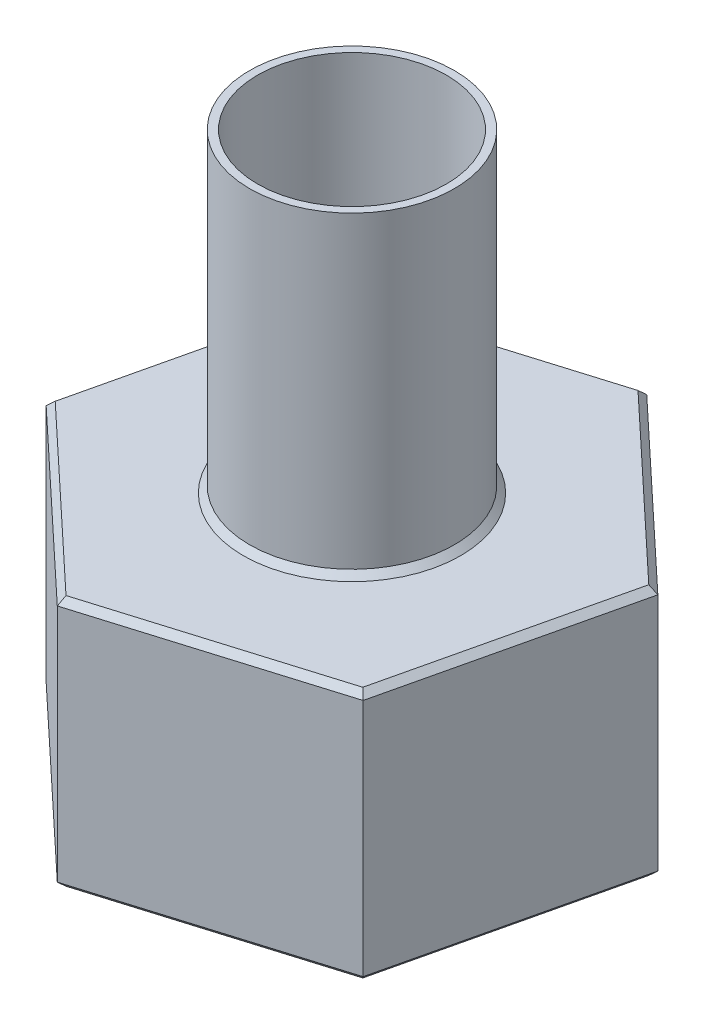
SolidWorks part; units mm, degrees
ref_plane "Front Plane" through (0, 0, 0) normal (0, 0, 1) x (1, 0, 0)
ref_plane "Top Plane" through (0, 0, 0) normal (0, 1, 0) x (1, 0, 0)
ref_plane "Right Plane" through (0, 0, 0) normal (1, 0, 0) x (0, 0, -1)
sketch "草图1" plane through (0, 0, 0) normal (0, 1, 0) x (1, 0, 0)
  circle A0 centre (0, 0) radius 3
  circle A1 centre (0, 0) radius 3.253
extrude "凸台-拉伸1" add sketch "草图1" along normal blind 10 contours A1
sketch "草图2" plane through (0, 0, 0) normal (0, -1, 0) x (1, 0, 0)
  circle A0 centre (0, 0) radius 3
extrude "切除-拉伸1" cut sketch "草图2" against normal blind 10
sketch "草图3" plane through (0, 0, 0) normal (0, -1, 0) x (1, 0, 0)
  line L13 (1.7746, -7.5895) -> (7.46, -2.2579)
  line L14 (7.46, -2.2579) -> (5.6854, 5.3316)
  line L15 (5.6854, 5.3316) -> (-1.7746, 7.5895)
  line L16 (-1.7746, 7.5895) -> (-7.46, 2.2579)
  line L17 (-7.46, 2.2579) -> (-5.6854, -5.3316)
  line L18 (-5.6854, -5.3316) -> (1.7746, -7.5895)
  circle A0 centre (0, 0) radius 6.75 construction
extrude "凸台-拉伸2" add sketch "草图3" along normal blind 8
chamfer "倒角2" distance 0.2 angle 45 13 edges at (4.6173, 0, -4.9237) (6.5727, 0, 1.5369) (1.9554, 0, 6.4606) (-4.6173, 0, 4.9237) (-6.5727, 0, -1.5369) (-1.9554, 0, -6.4606) (0, 0, 3.253) (-1.9554, -8, -6.4606) (4.6173, -8, -4.9237) (6.5727, -8, 1.5369) (1.9554, -8, 6.4606) (-4.6173, -8, 4.9237) (-6.5727, -8, -1.5369)
sketch "草图6" plane through (0, -8, 0) normal (0, -1, 0) x (1, 0, 0)
  circle A0 centre (0, 0) radius 6.35
extrude "切除-拉伸3" cut sketch "草图6" against normal blind 7.5
scale "缩放比例1" scale about centroid uniform scaling yes scale factor 1.703704
